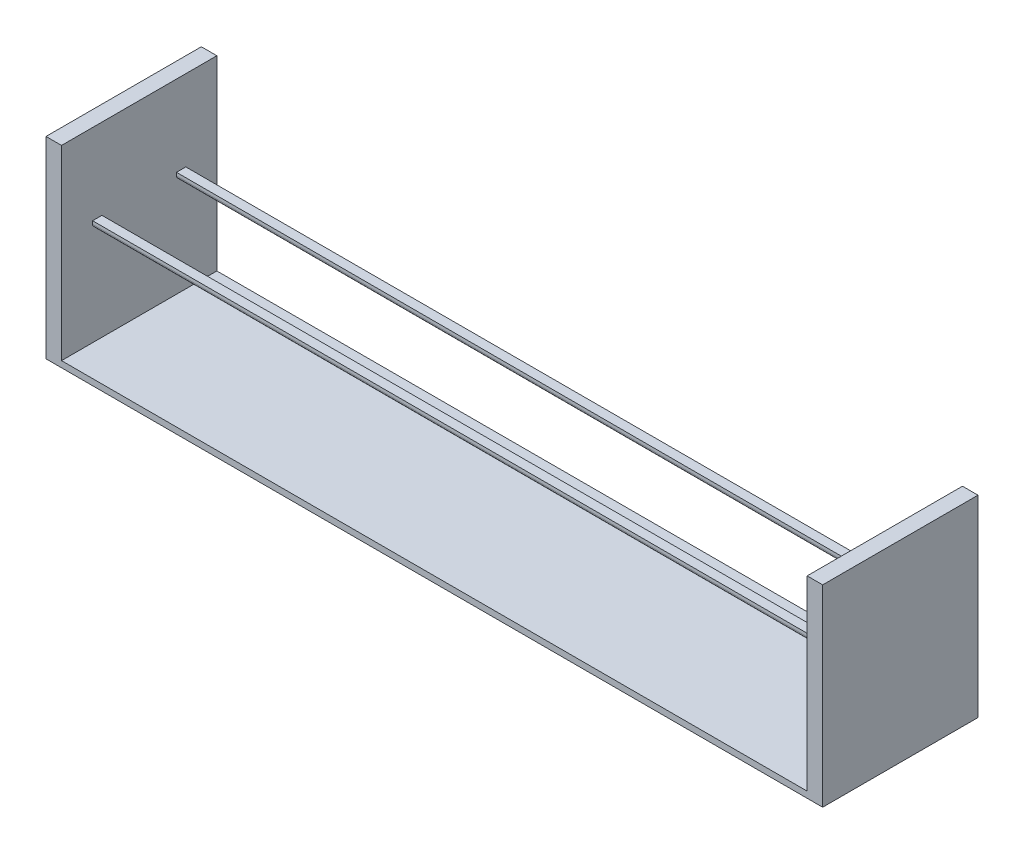
SolidWorks part; units mm, degrees
ref_plane "Front Plane" through (0, 0, 0) normal (0, 0, 1) x (1, 0, 0)
ref_plane "Top Plane" through (0, 0, 0) normal (0, 1, 0) x (1, 0, 0)
ref_plane "Right Plane" through (0, 0, 0) normal (1, 0, 0) x (0, 0, -1)
sketch "Sketch2" plane through (0, 0, 0) normal (0, 1, 0) x (1, 0, 0)
  line L1 (-78.4367, 22.1468) -> (1171.5633, 22.1468)
  line L2 (-78.4367, 22.1468) -> (-78.4367, -227.8532)
  line L3 (-78.4367, -227.8532) -> (1171.5633, -227.8532)
  line L4 (1171.5633, 22.1468) -> (1171.5633, -227.8532)
  line L5 (-78.4367, 22.1468) -> (1171.5633, -227.8532) construction
  line L6 (-78.4367, -227.8532) -> (1171.5633, 22.1468) construction
  point P0 (546.5633, -102.8532)
extrude "Boss-Extrude1" add sketch "Sketch2" along normal blind 10
sketch "Sketch3" plane through (0, 10, 0) normal (0, 1, 0) x (1, 0, 0)
  line L0 (-78.4367, -227.8532) -> (1171.5633, -227.8532) construction
  line L1 (-78.4367, 22.1468) -> (-53.4367, 22.1468)
  line L2 (-78.4367, 22.1468) -> (-78.4367, -227.8532)
  line L3 (-78.4367, -227.8532) -> (-53.4367, -227.8532)
  line L4 (-53.4367, 22.1468) -> (-53.4367, -227.8532)
  line L6 (1171.5633, 22.1468) -> (1146.5633, 22.1468)
  line L7 (1171.5633, 22.1468) -> (1171.5633, -227.8532)
  line L8 (1171.5633, -227.8532) -> (1146.5633, -227.8532)
  line L9 (1146.5633, 22.1468) -> (1146.5633, -227.8532)
extrude "Boss-Extrude2" add sketch "Sketch3" along normal blind 300
sketch "Sketch4" plane through (-53.4367, 0, 0) normal (1, 0, 0) x (0, 0, -1)
  line L0 (-102.8532, 310) -> (-102.8532, -15.7725) construction
  line L5 (-177.8532, 180) -> (-162.8532, 180)
  line L6 (-177.8532, 180) -> (-177.8532, 170)
  line L7 (-177.8532, 170) -> (-162.8532, 170)
  line L8 (-162.8532, 180) -> (-162.8532, 170)
  line L9 (-227.8532, 310) -> (22.1468, 310) construction
  line L10 (-27.8532, 180) -> (-27.8532, 170)
  line L11 (-27.8532, 170) -> (-42.8532, 170)
  line L12 (-42.8532, 180) -> (-42.8532, 170)
  line L13 (-27.8532, 180) -> (-42.8532, 180)
extrude "Boss-Extrude3" add sketch "Sketch4" along normal blind 1200
fillet "Fillet1" radius 5 2 edges at (546.5633, 170, 162.8532) (546.5633, 170, 177.8532)
fillet "Fillet3" radius 5 2 edges at (546.5633, 170, 27.8532) (546.5633, 170, 42.8532)
